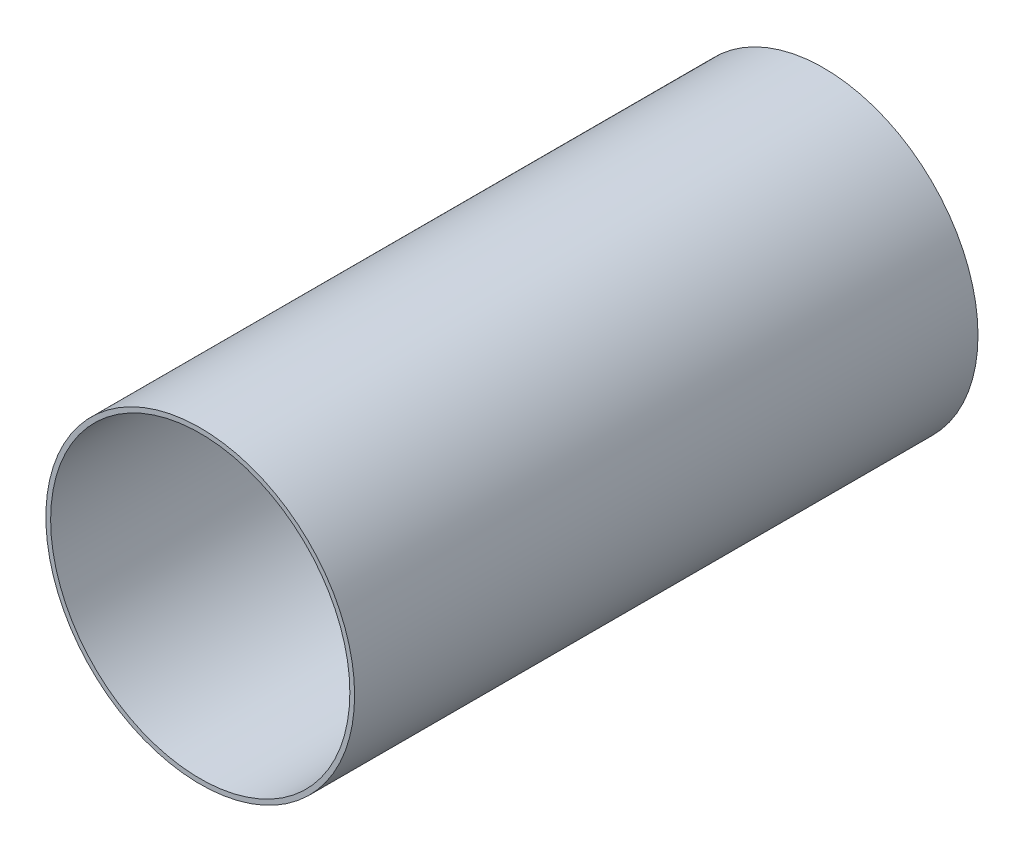
SolidWorks part; units mm, degrees
ref_plane "Front Plane" through (0, 0, 0) normal (1, 0, 0) x (0, 1, 0)
ref_plane "Top Plane" through (0, 0, 0) normal (0, 0, 1) x (0, 1, 0)
ref_plane "Right Plane" through (0, 0, 0) normal (0, 1, 0) x (-1, 0, 0)
sketch "Sketch1" plane through (0, 0, 0) normal (0, 0, 1) x (0, 1, 0)
  circle A0 centre (0, 0) radius 49.53
  circle A1 centre (0, 0) radius 48
  dimension "D1" = 99.06
  dimension "D2" = 1.53
extrude "Boss-Extrude1" add sketch "Sketch1" along normal blind 200
